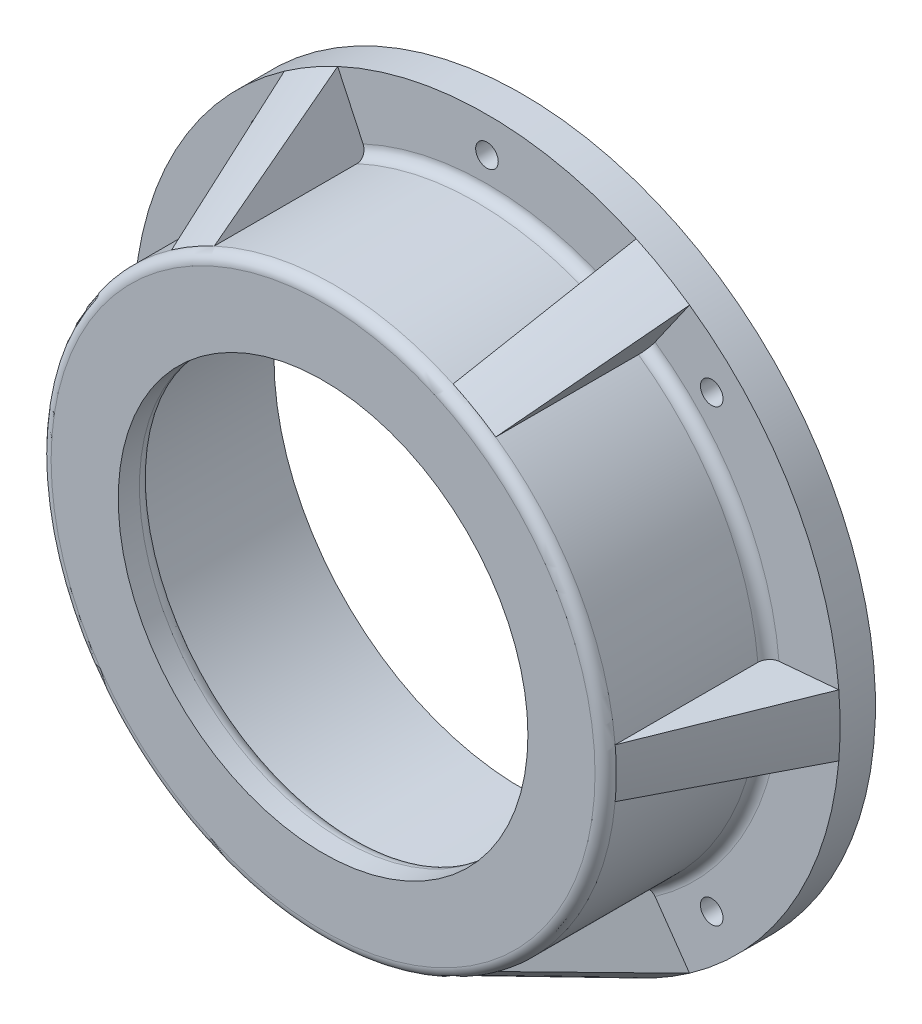
SolidWorks part; units mm, degrees
material "ABS"
ref_plane "前视基准面" through (0, 0, 0) normal (0, 0, 1) x (1, 0, 0)
ref_plane "上视基准面" through (0, 0, 0) normal (0, 1, 0) x (1, 0, 0)
ref_plane "右视基准面" through (0, 0, 0) normal (1, 0, 0) x (0, 0, -1)
sketch "草图1" plane through (0, 0, 0) normal (0, 0, 1) x (1, 0, 0)
  circle A0 centre (0, 0) radius 35.15
  circle A1 centre (0, 0) radius 40
  dimension "D1" = 70.3
  dimension "D2" = 80
extrude "凸台-拉伸1" add sketch "草图1" along normal blind 28.2
sketch "草图2" plane through (0, 0, 28.2) normal (0, 0, 1) x (1, 0, 0)
  circle A0 centre (0, 0) radius 35.5
  circle A1 centre (0, 0) radius 29
  dimension "D1" = 71
  dimension "D2" = 58
extrude "凸台-拉伸2" add sketch "草图2" against normal blind 5
sketch "草图3" plane through (0, 0, 0) normal (0, 0, -1) x (-1, 0, 0)
  circle A0 centre (0, 0) radius 40
  circle A1 centre (0, 0) radius 50
  dimension "D1" = 80
  dimension "D2" = 100
extrude "凸台-拉伸3" add sketch "草图3" against normal blind 5
sketch "草图4" plane through (0, 0, 5) normal (0, 0, 1) x (1, 0, 0)
  line L0 (0, 0) -> (0, 45) construction
  line L1 (0, 0) -> (50, 0) construction
  line L2 (31.8198, 31.8198) -> (0, 0) construction
  circle A0 centre (0, 0) radius 45 construction
  circle A1 centre (0, 0) radius 50 construction
  circle A2 centre (31.8198, 31.8198) radius 1.6
  circle A3 centre (31.8198, -31.8198) radius 1.6
  circle A4 centre (-31.8198, -31.8198) radius 1.6
  circle A5 centre (-31.8198, 31.8198) radius 1.6
  circle A6 centre (0, 45) radius 1.6
  circle A7 centre (0, -45) radius 1.6
  point P19 (0, 0)
  dimension "D1" = 90
  dimension "D2" = 45
  dimension "D3" = 3.2
  dimension "D5" = 3.2
  dimension "D4" = 4
extrude "切除-拉伸1" cut sketch "草图4" against normal through all
fillet "圆角1" radius 1.5 2 edges at (35.15, 0, 23.2) (40, 0, 28.2)
fillet "圆角2" radius 2 1 edges at (29, 0, 23.2)
sketch "草图5" plane through (0, 0, 0) normal (0, 1, 0) x (1, 0, 0)
  line L0 (-50, -5) -> (-40, -26.7)
  line L1 (40, -26.7) -> (-40, -26.7) construction
  line L2 (-40, -26.7) -> (-40, -5)
  line L3 (-40, -5) -> (-50, -5)
ref_axis "基准轴1" through (0, 0, -1.41) along (0, 0, 1)
revolve "旋转1" add sketch "草图5" angle 10 mid plane about axis through (0, 0, -1.41) along (0, 0, 1)
pattern_circular "阵列(圆周)1" count 6 every 60 about axis through (0, 0, 0) along (0, 0, 1) of "旋转1"
fillet "圆角3" radius 1.5 6 edges at (34.641, 20, 5) (0, 40, 5) (-34.641, 20, 5) (-34.641, -20, 5) (0, -40, 5) (34.641, -20, 5)
